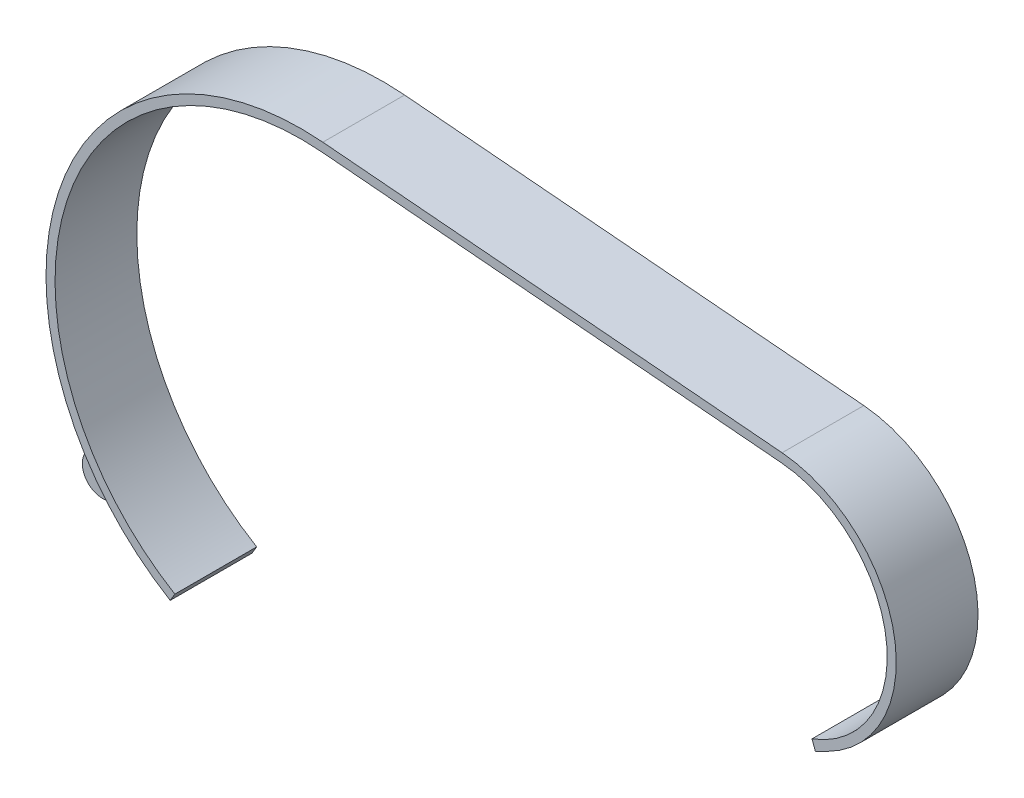
SolidWorks part; units mm, degrees
ref_plane "Front Plane" through (0, 0, 0) normal (0, 0, 1) x (1, 0, 0)
ref_plane "Top Plane" through (0, 0, 0) normal (0, 1, 0) x (1, 0, 0)
ref_plane "Right Plane" through (0, 0, 0) normal (1, 0, 0) x (0, 0, -1)
sketch "Sketch1" plane through (0, 0, 0) normal (0, 0, 1) x (1, 0, 0)
  line L0 (121.6679, 181.2951) -> (282.8673, 167.4918)
  line L1 (153.0564, 18.0749) -> (297.6383, 90.6823)
  line L2 (283.1381, 170.6552) -> (121.9388, 184.4585)
  line L3 (154.4813, 15.2376) -> (299.0632, 87.845)
  line L4 (36.5877, 50.783) -> (13.6453, 23.6139)
  line L5 (53.8588, 29.1942) -> (22.3162, 12.7753)
  line L6 (68.3731, 18.3914) -> (160.7614, 18.3914) construction
  line L7 (114.3, 95.25) -> (68.3731, 18.3914)
  line L8 (294.8392, 85.7238) -> (264.7021, 85.7238) construction
  line L9 (279.4, 127) -> (294.8392, 85.7238)
  circle A1 centre (19.05, 19.05) radius 3.2639 construction
  circle A2 centre (19.05, 19.05) radius 3.2639
  circle A3 centre (19.05, 19.05) radius 7.0739
  arc A4 (25.1637, 15.4915) -> (15.2029, 24.9863) centre (19.05, 19.05) ccw construction
  arc A5 (25.1637, 15.4915) -> (15.2029, 24.9863) centre (19.05, 19.05) ccw
  circle A6 centre (279.4, 127) radius 20.2311 construction
  circle A7 centre (279.4, 127) radius 20.2311
  circle A8 centre (279.4, 127) radius 40.64
  circle A9 centre (114.3, 95.25) radius 35.7643 construction
  circle A10 centre (114.3, 95.25) radius 35.7643
  circle A11 centre (114.3, 95.25) radius 86.36
  circle A12 centre (114.3, 95.25) radius 89.535
  circle A13 centre (279.4, 127) radius 43.815
  arc A14 (117.9296, 28.7195) -> (118.5852, 20.7913) centre (113.7881, 24.3858) ccw construction
  arc A15 (117.9296, 28.7195) -> (118.5852, 20.7913) centre (113.7881, 24.3858) ccw construction
  arc A16 (261.4121, 86.1246) -> (257.9665, 92.9191) centre (263.5195, 91.4642) ccw construction
  arc A17 (261.4121, 86.1246) -> (257.9665, 92.9191) centre (263.5195, 91.4642) ccw construction
  dimension "D1" = 81.28
  dimension "D2" = 172.72
  dimension "D3" = 3.175
  dimension "D4" = 3.175
  dimension "D5" = 35.56
  dimension "D6" = 35.56
extrude "Boss-Extrude1" add sketch "Sketch1" along normal blind 25.4 contours A13 L0 A8 L1 L9 | A8 L9 L1 | A13 L9 L3 | A13 L2 A12 L0 | L0 A12 L7 A11
sketch "Sketch2" plane through (0, 0, 0) normal (0, 0, -1) x (-1, 0, 0)
  line L0 (-114.3, 95.25) -> (-68.3731, 18.3914) construction
  line L1 (-121.6679, 181.2951) -> (-282.8673, 167.4918) construction
  line L2 (-53.8588, 29.1942) -> (-22.3162, 12.7753) construction
  line L3 (-36.5877, 50.783) -> (-13.6453, 23.6139) construction
  line L4 (-154.4813, 15.2376) -> (-299.0632, 87.845) construction
  line L5 (-283.1381, 170.6552) -> (-121.9388, 184.4585) construction
  line L6 (-153.0564, 18.0749) -> (-297.6383, 90.6823) construction
  line L7 (-279.4, 127) -> (-294.8392, 85.7238) construction
  line L8 (-114.3, 95.25) -> (-68.3731, 18.3914)
  line L9 (-121.6679, 181.2951) -> (-282.8673, 167.4918)
  line L10 (-53.8588, 29.1942) -> (-22.3162, 12.7753)
  line L11 (-36.5877, 50.783) -> (-13.6453, 23.6139)
  line L12 (-154.4813, 15.2376) -> (-299.0632, 87.845)
  line L13 (-283.1381, 170.6552) -> (-121.9388, 184.4585)
  line L14 (-153.0564, 18.0749) -> (-297.6383, 90.6823)
  line L15 (-279.4, 127) -> (-294.8392, 85.7238)
  arc A0 (-15.2029, 24.9863) -> (-25.1637, 15.4915) centre (-19.05, 19.05) ccw construction
  circle A1 centre (-114.3, 95.25) radius 86.36
  circle A2 centre (-114.3, 95.25) radius 86.36
  circle A3 centre (-114.3, 95.25) radius 35.7643
  circle A4 centre (-114.3, 95.25) radius 35.7643
  circle A5 centre (-279.4, 127) radius 40.64
  circle A6 centre (-279.4, 127) radius 40.64
  circle A7 centre (-279.4, 127) radius 20.2311
  circle A8 centre (-279.4, 127) radius 20.2311
  circle A9 centre (-19.05, 19.05) radius 7.0739
  circle A10 centre (-19.05, 19.05) radius 7.0739
  circle A11 centre (-19.05, 19.05) radius 3.2639
  circle A12 centre (-19.05, 19.05) radius 3.2639
  circle A13 centre (-279.4, 127) radius 43.815
  circle A14 centre (-279.4, 127) radius 43.815
  circle A15 centre (-114.3, 95.25) radius 89.535
  circle A16 centre (-114.3, 95.25) radius 89.535
  arc A17 (-15.2029, 24.9863) -> (-25.1637, 15.4915) centre (-19.05, 19.05) ccw
  arc M16 (-68.3731, 18.3914) -> (-121.9388, 184.4585) centre (-114.3, 95.25) ccw
  dimension "D1" = 0
  dimension "D2" = 0
  dimension "D3" = 0
  dimension "D4" = 0
  dimension "D5" = 0
  dimension "D6" = 0
  dimension "D7" = 0
  dimension "D8" = 0
extrude "Boss-Extrude2" add sketch "Sketch2" against normal blind 3.175 contours A10 L11 L10 M16 | A10 A12
sketch "Sketch3" plane through (0, 0, 25.4) normal (0, 0, 1) x (1, 0, 0)
  line L0 (114.3, 95.25) -> (68.3731, 18.3914) construction
  line L1 (121.6679, 181.2951) -> (282.8673, 167.4918) construction
  line L2 (53.8588, 29.1942) -> (22.3162, 12.7753) construction
  line L3 (36.5877, 50.783) -> (13.6453, 23.6139) construction
  line L4 (154.4813, 15.2376) -> (299.0632, 87.845) construction
  line L5 (283.1381, 170.6552) -> (121.9388, 184.4585) construction
  line L6 (153.0564, 18.0749) -> (297.6383, 90.6823) construction
  line L7 (279.4, 127) -> (294.8392, 85.7238) construction
  line L8 (114.3, 95.25) -> (68.3731, 18.3914)
  line L9 (121.6679, 181.2951) -> (282.8673, 167.4918)
  line L10 (53.8588, 29.1942) -> (22.3162, 12.7753)
  line L11 (36.5877, 50.783) -> (13.6453, 23.6139)
  line L12 (154.4813, 15.2376) -> (299.0632, 87.845)
  line L13 (283.1381, 170.6552) -> (121.9388, 184.4585)
  line L14 (153.0564, 18.0749) -> (297.6383, 90.6823)
  line L15 (279.4, 127) -> (294.8392, 85.7238)
  arc A0 (25.1637, 15.4915) -> (15.2029, 24.9863) centre (19.05, 19.05) ccw construction
  circle A1 centre (114.3, 95.25) radius 86.36
  circle A2 centre (114.3, 95.25) radius 86.36
  circle A3 centre (114.3, 95.25) radius 35.7643
  circle A4 centre (114.3, 95.25) radius 35.7643
  circle A5 centre (279.4, 127) radius 40.64
  circle A6 centre (279.4, 127) radius 40.64
  circle A7 centre (279.4, 127) radius 20.2311
  circle A8 centre (279.4, 127) radius 20.2311
  circle A9 centre (19.05, 19.05) radius 7.0739
  circle A10 centre (19.05, 19.05) radius 7.0739
  circle A11 centre (19.05, 19.05) radius 3.2639
  circle A12 centre (19.05, 19.05) radius 3.2639
  circle A13 centre (279.4, 127) radius 43.815
  circle A14 centre (279.4, 127) radius 43.815
  circle A15 centre (114.3, 95.25) radius 89.535
  circle A16 centre (114.3, 95.25) radius 89.535
  arc A17 (25.1637, 15.4915) -> (15.2029, 24.9863) centre (19.05, 19.05) ccw
  arc M9 (299.0632, 87.845) -> (283.1381, 170.6552) centre (279.4, 127) ccw
  line M10 (283.1381, 170.6552) -> (121.9388, 184.4585)
  arc M11 (121.9388, 184.4585) -> (68.3731, 18.3914) centre (114.3, 95.25) ccw
  line M12 (68.3731, 18.3914) -> (70.0017, 21.1169)
  arc M13 (70.0017, 21.1169) -> (121.6679, 181.2951) centre (114.3, 95.25) cw
  line M14 (121.6679, 181.2951) -> (282.8673, 167.4918)
  arc M15 (282.8673, 167.4918) -> (293.6378, 88.9357) centre (279.4, 127) cw
  line M16 (293.6378, 88.9357) -> (294.8392, 85.7238)
  line M17 (294.8392, 85.7238) -> (299.0632, 87.845)
  dimension "D1" = 0
  dimension "D2" = 0
  dimension "D3" = 0
  dimension "D4" = 0
  dimension "D5" = 0
  dimension "D6" = 0
  dimension "D7" = 0
  dimension "D8" = 0
extrude "Boss-Extrude3" add sketch "Sketch3" along normal blind 3.302 contours A16 M14 M11 M12 M13 | A16 L9 A14 M10 | A14 L9 L14 M9 M15 M16 | L14 M16 M15 | A14 L15 M17 | A2
